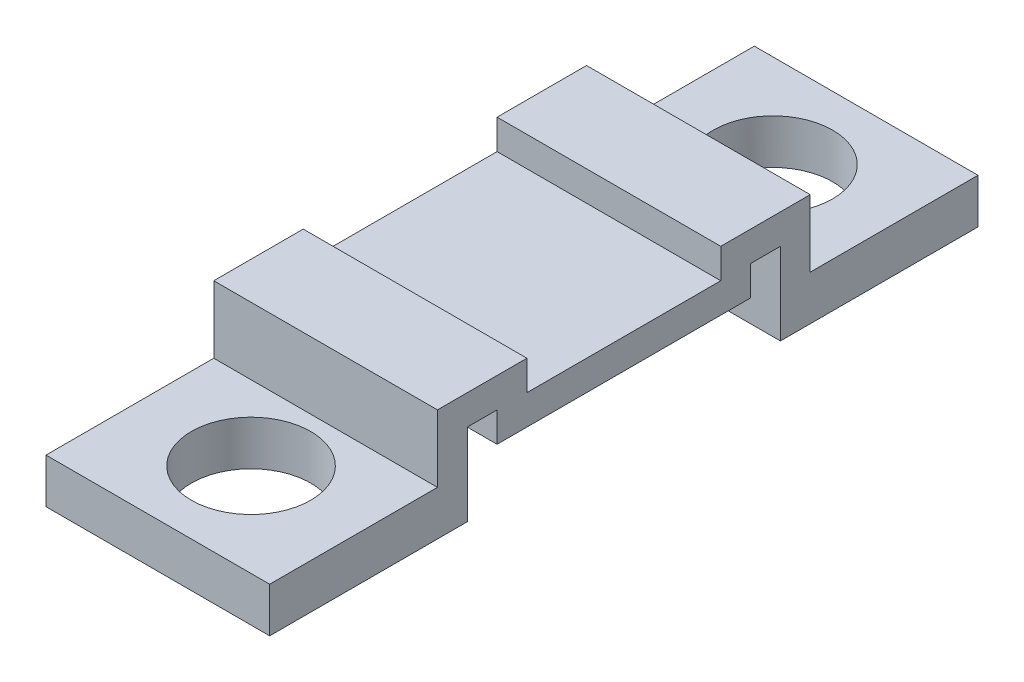
SolidWorks part; units mm, degrees
ref_plane "Front Plane" through (0, 0, 0) normal (0, 0, 1) x (1, 0, 0)
ref_plane "Top Plane" through (0, 0, 0) normal (0, 1, 0) x (1, 0, 0)
ref_plane "Right Plane" through (0, 0, 0) normal (1, 0, 0) x (0, 0, -1)
sketch "Sketch4" plane through (0, 0, 0) normal (1, 0, 0) x (0, 0, -1)
  line L20 (-5, -1) -> (-5, 0.8)
  line L21 (-5, 0.8) -> (-2.6, 0.8)
  line L22 (-2.6, 0.8) -> (-2.6, 0)
  line L29 (-4.2, 0) -> (-3.4, 0)
  line L30 (-3.4, 0) -> (-3.4, -0.8)
  line L32 (0, -0.8) -> (0, 0) construction
  line L46 (-4.2, 0) -> (-4.2, -2.2)
  line L47 (-4.2, -2.2) -> (-9.5, -2.2)
  line L48 (-9.5, -2.2) -> (-9.5, -1)
  line L49 (-9.5, -1) -> (-5, -1)
  line L51 (-2.6, 0) -> (2.6, 0)
  line L52 (-3.4, -0.8) -> (3.4, -0.8)
  line L53 (9.5, -1) -> (5, -1)
  line L54 (9.5, -2.2) -> (9.5, -1)
  line L55 (4.2, -2.2) -> (9.5, -2.2)
  line L56 (4.2, 0) -> (4.2, -2.2)
  line L57 (3.4, 0) -> (3.4, -0.8)
  line L58 (4.2, 0) -> (3.4, 0)
  line L59 (2.6, 0.8) -> (2.6, 0)
  line L60 (5, 0.8) -> (2.6, 0.8)
  line L61 (5, -1) -> (5, 0.8)
  point P19 (4.5, -2)
  point P20 (4.5, 2)
  dimension "D1" = 1.2
  dimension "D2" = 0.8
  dimension "D3" = 2.4
  dimension "D5" = 0.8
  dimension "D6" = 5.2
  dimension "D7" = 1.8
  dimension "D8" = 0.8
  dimension "D9" = 19
extrude "Boss-Extrude4" add sketch "Sketch4" along normal mid plane 6
sketch "Sketch5" plane through (0, -1, 0) normal (0, 1, 0) x (1, 0, 0)
  line L0 (-3, 0) -> (3, 0) construction
  line L1 (-3, 2.6) -> (-3, -2.6) construction
  line L2 (3, 2.6) -> (3, -2.6) construction
  circle A1 centre (0, -7) radius 1.6
  circle A2 centre (0, 7) radius 1.6
  dimension "D2" = 14
  dimension "D1" = 3.2
extrude "Cut-Extrude1" cut sketch "Sketch5" against normal up to next
